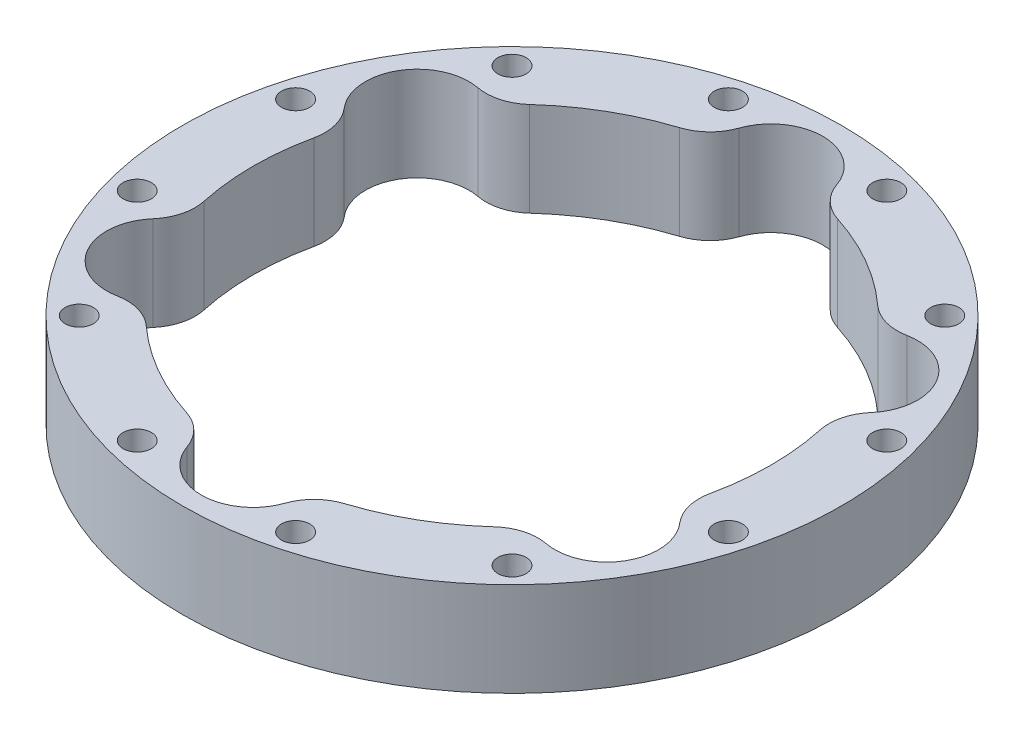
SolidWorks part; units mm, degrees
ref_plane "Front Plane" through (0, 0, 0) normal (0, 0, 1) x (1, 0, 0)
ref_plane "Top Plane" through (0, 0, 0) normal (0, 1, 0) x (1, 0, 0)
ref_plane "Right Plane" through (0, 0, 0) normal (1, 0, 0) x (0, 0, -1)
sketch "Sketch1" plane through (0, 0, 0) normal (0, 1, 0) x (1, 0, 0)
  line L0 (-49.1682, 0) -> (0, 0) construction
  line L1 (0, 0) -> (-48.4521, -12.9827) construction
  circle A0 centre (0, 0) radius 35
  circle A1 centre (0, 0) radius 32.5 construction
  circle A2 centre (0, 0) radius 27.5
  circle A3 centre (0, 27.5) radius 5.5
  circle A4 centre (23.8157, 13.75) radius 5.5
  circle A5 centre (23.8157, -13.75) radius 5.5
  circle A6 centre (0, -27.5) radius 5.5
  circle A7 centre (-23.8157, -13.75) radius 5.5
  circle A8 centre (-23.8157, 13.75) radius 5.5
  circle A9 centre (-31.3926, -8.4116) radius 1.5
  circle A10 centre (-31.3926, 8.4116) radius 1.5
  circle A11 centre (-22.981, 22.981) radius 1.5
  circle A12 centre (-8.4116, 31.3926) radius 1.5
  circle A13 centre (8.4116, 31.3926) radius 1.5
  circle A14 centre (22.981, 22.981) radius 1.5
  circle A15 centre (31.3926, 8.4116) radius 1.5
  circle A16 centre (31.3926, -8.4116) radius 1.5
  circle A17 centre (22.981, -22.981) radius 1.5
  circle A18 centre (8.4116, -31.3926) radius 1.5
  circle A19 centre (-8.4116, -31.3926) radius 1.5
  circle A20 centre (-22.981, -22.981) radius 1.5
  point P19 (0, 0)
  point P47 (0, 0)
  dimension "D1" = 70
  dimension "D2" = 65
  dimension "D3" = 55
  dimension "D4" = 11
  dimension "D7" = 3
  dimension "D6" = 15
  dimension "D5" = 6
  dimension "D8" = 12
extrude "Boss-Extrude1" add sketch "Sketch1" along normal blind 10 contours A0 A20 A19 A18 A17 A16 A15 A14 A13 A12 A11 A10 A9 A8 A2 A3 A4 A5 A6 A7
fillet "Fillet1" radius 5 12 edges at (5.4724, 5, -26.95) (-5.4724, 5, -26.95) (26.0756, 5, -8.7357) (20.6032, 5, -18.2143) (20.6032, 5, 18.2143) (26.0756, 5, 8.7357) (-5.4724, 5, 26.95) (5.4724, 5, 26.95) (-26.0756, 5, 8.7357) (-20.6032, 5, 18.2143) (-20.6032, 5, -18.2143) (-26.0756, 5, -8.7357)
